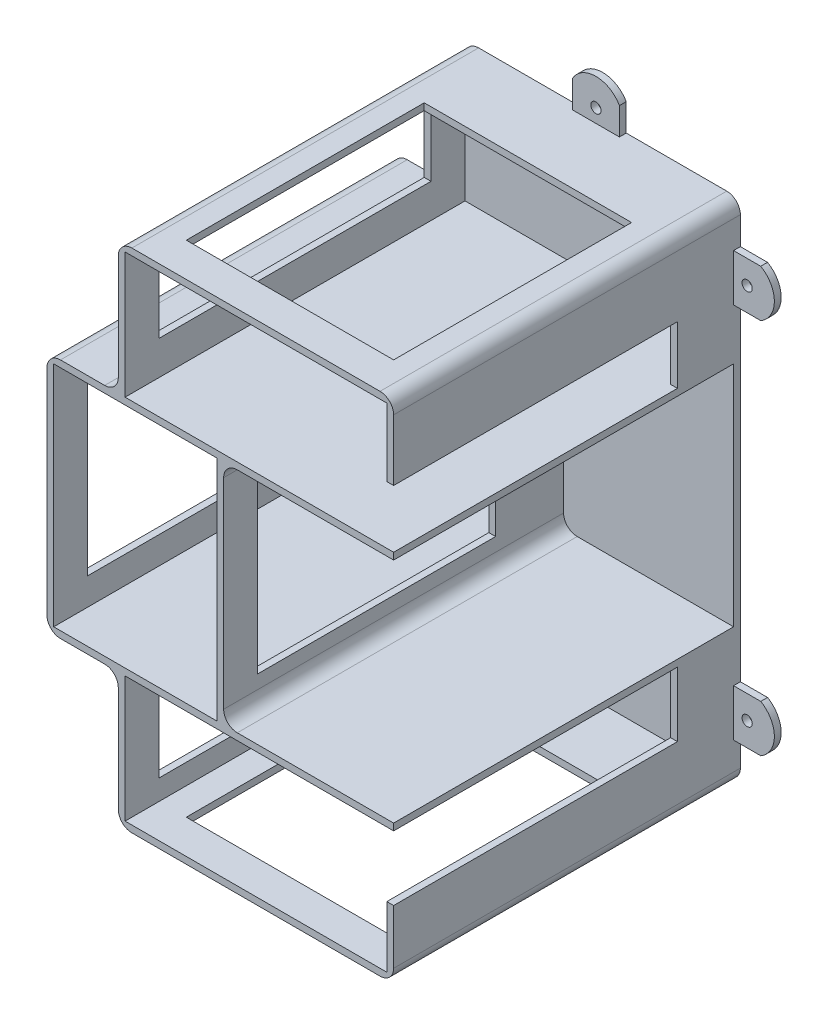
SolidWorks part; units mm, degrees
other "Marquage1"
sketch "Esquisse17" plane through (0, -52.2, -65) normal (-0.4358, -0.0146, -0.8999) x (-0.2736, 0.9547, 0.117)
ref_plane "Plan de face" through (0, 0, 0) normal (0, 0, 1) x (1, 0, 0)
ref_plane "Plan de dessus" through (0, 0, 0) normal (0, 1, 0) x (1, 0, 0)
ref_plane "Plan de droite" through (0, 0, 0) normal (1, 0, 0) x (0, 0, -1)
sketch "Esquisse27" plane through (0, 0, 0) normal (0, 0, 1) x (1, 0, 0)
  line L28 (148.5, -72.5) -> (67.5, -72.5)
  line L29 (67.5, -72.5) -> (67.5, -33.5)
  line L30 (148.5, 76.5) -> (67.5, 76.5)
  line L31 (67.5, 76.5) -> (67.5, 37.5)
  line L32 (67.5, -33.5) -> (46.5, -33.5)
  line L33 (46.5, -33.5) -> (46.5, 37.5)
  line L34 (46.5, 37.5) -> (67.5, 37.5)
  line L35 (148.5, 35.5) -> (98.5, 35.5)
  line L36 (98.5, 35.5) -> (98.5, -31.5)
  line L37 (98.5, -31.5) -> (148.5, -31.5)
  line L38 (148.5, 76.5) -> (148.5, 35.5)
  line L39 (148.5, -72.5) -> (148.5, -31.5)
  dimension "D1" = 81
  dimension "D2" = 149
  dimension "D3" = 71
  dimension "D4" = 50
  dimension "D5" = 21
  dimension "D6" = 76.5
  dimension "D7" = 81
  dimension "D8" = 67
  dimension "D9" = 50
  dimension "D10" = 41
  dimension "D11" = 39
  dimension "D12" = 39
  dimension "D13" = 21
  dimension "D14" = 46.5
extrude "Boss.-Extru.9" add sketch "Esquisse27" along normal blind 100
sketch "Esquisse31" plane through (0, 0, 100) normal (0, 0, 1) x (1, 0, 0)
  line L5 (148.5, -72.5) -> (148.5, -31.5) construction
  line L25 (148.5, -31.5) -> (98.5, -31.5) construction
  line L26 (46.5, 37.5) -> (46.5, -33.5) construction
  line L29 (98.5, -31.5) -> (98.5, 35.5) construction
  line L31 (67.5, -33.5) -> (67.5, -72.5) construction
  line L32 (67.5, -72.5) -> (148.5, -72.5) construction
  line L33 (148.5, 35.5) -> (148.5, 76.5) construction
  line L34 (98.5, 35.5) -> (148.5, 35.5) construction
  line L35 (148.5, 76.5) -> (67.5, 76.5) construction
  line L36 (67.5, 76.5) -> (67.5, 37.5) construction
  line L40 (69.5, 74.5) -> (69.5, 37.5)
  line L41 (48.5, -31.5) -> (48.5, 35.5)
  line L42 (69.5, -70.5) -> (69.5, -33.5)
  line L43 (146.5, 74.5) -> (69.5, 74.5)
  line L44 (146.5, 37.5) -> (146.5, 74.5)
  line L45 (96.5, 35.5) -> (96.5, -31.5)
  line L46 (146.5, -70.5) -> (146.5, -33.5)
  line L47 (69.5, -70.5) -> (146.5, -70.5)
  line L48 (96.5, -31.5) -> (48.5, -31.5)
  line L49 (96.5, 35.5) -> (48.5, 35.5)
  line L50 (146.5, -33.5) -> (69.5, -33.5)
  line L51 (146.5, 37.5) -> (69.5, 37.5)
  point P12 (109.5, 104.5)
  dimension "D1" = 2
  dimension "D2" = 2
  dimension "D3" = 2
  dimension "D4" = 2
  dimension "D5" = 2
  dimension "D6" = 2
  dimension "D7" = 2
  dimension "D8" = 2
  dimension "D9" = 2
  dimension "D10" = 2
  dimension "D11" = 2
  dimension "D12" = 2
extrude "Enlèv. mat.-Extru.17" cut sketch "Esquisse31" against normal blind 100
sketch "Esquisse35" plane through (0, -72.5, 0) normal (0, -1, 0) x (1, 0, 0)
  line L0 (148.5, 100) -> (148.5, 0) construction
  line L5 (67.5, 100) -> (67.5, 0) construction
  line L6 (67.5, 100) -> (148.5, 100) construction
  line L7 (67.5, 0) -> (148.5, 0) construction
  line L10 (77.5, 90) -> (138.5, 90)
  line L11 (77.5, 90) -> (77.5, 20)
  line L12 (77.5, 20) -> (138.5, 20)
  line L13 (138.5, 90) -> (138.5, 20)
  dimension "D1" = 10
  dimension "D2" = 10
  dimension "D3" = 10
  dimension "D4" = 20
extrude "Enlèv. mat.-Extru.20" cut sketch "Esquisse35" against normal blind 2
sketch "Esquisse36" plane through (67.5, 0, 0) normal (-1, 0, 0) x (0, 0, 1)
  line L0 (100, 76.5) -> (100, 37.5) construction
  line L2 (100, 76.5) -> (0, 76.5) construction
  line L3 (10, 47.5) -> (90, 47.5)
  line L4 (10, 47.5) -> (10, 68.5)
  line L5 (10, 68.5) -> (90, 68.5)
  line L6 (90, 47.5) -> (90, 68.5)
  line L7 (0, 76.5) -> (0, 37.5) construction
  line L8 (100, 37.5) -> (0, 37.5) construction
  line L14 (100, -33.5) -> (0, -33.5) construction
  line L25 (100, -33.5) -> (100, -72.5) construction
  line L26 (10, -64.5) -> (90, -64.5)
  line L27 (10, -64.5) -> (10, -43.5)
  line L28 (10, -43.5) -> (90, -43.5)
  line L29 (90, -64.5) -> (90, -43.5)
  line L30 (100, -72.5) -> (0, -72.5) construction
  line L32 (0, -33.5) -> (0, -72.5) construction
  point P2 (0, 69.5875)
  point P8 (97.8468, -33.5)
  point P9 (100, -57.2204)
  point P10 (79.7693, 37.5)
  point P18 (0, -48.009)
  point P19 (0, -42.1912)
  point P22 (100, -72.5)
  point P24 (76.4193, 76.5)
  point P26 (100, 53.6257)
  dimension "D1" = 8
  dimension "D2" = 10
  dimension "D3" = 10
  dimension "D4" = 10
  dimension "D5" = 8
  dimension "D6" = 10
  dimension "D7" = 10
  dimension "D8" = 10
sketch "Esquisse37" plane through (46.5, 0, 0) normal (-1, 0, 0) x (0, 0, 1)
  line L0 (-31.1815, 125) -> (105.2441, 125) construction
  line L1 (0, 37.5) -> (0, -33.5) construction
  line L2 (20, 27.5) -> (90, 27.5)
  line L3 (20, 27.5) -> (20, -23.5)
  line L4 (20, -23.5) -> (90, -23.5)
  line L5 (90, 27.5) -> (90, -23.5)
  line L6 (100, 37.5) -> (0, 37.5) construction
  line L7 (100, 37.5) -> (100, -33.5) construction
  line L8 (100, -33.5) -> (0, -33.5) construction
  dimension "D1" = 20
  dimension "D2" = 10
  dimension "D3" = 10
  dimension "D4" = 10
extrude "Enlèv. mat.-Extru.22" cut sketch "Esquisse37" against normal blind 52
sketch "Esquisse38" plane through (0, 76.5, 0) normal (0, 1, 0) x (1, 0, 0)
  line L0 (148.5, -100) -> (148.5, 0) construction
  line L5 (148.5, 0) -> (67.5, 0) construction
  line L6 (148.5, -100) -> (67.5, -100) construction
  line L7 (67.5, -100) -> (67.5, 0) construction
  line L12 (77.5, -90) -> (138.5, -90)
  line L13 (77.5, -90) -> (77.5, -20)
  line L14 (77.5, -20) -> (138.5, -20)
  line L15 (138.5, -90) -> (138.5, -20)
  dimension "D1" = 10
  dimension "D2" = 20
  dimension "D3" = 10
  dimension "D4" = 10
extrude "Enlèv. mat.-Extru.23" cut sketch "Esquisse38" against normal blind 2
sketch "Esquisse39" plane through (148.5, 0, 0) normal (1, 0, 0) x (0, 0, -1)
  line L5 (-100, 35.5) -> (-100, 76.5) construction
  line L14 (-100, 54.5) -> (-16.5, 54.5)
  line L20 (-100, 76.5) -> (0, 76.5) construction
  line L23 (-100, -52.5) -> (-16.5, -52.5)
  line L35 (-100, -72.5) -> (0, -72.5) construction
  line L40 (0, 35.5) -> (0, 76.5) construction
  line L41 (-16.5, 54.5) -> (-16.5, 37.5)
  line L42 (-16.5, 37.5) -> (-100, 37.5)
  line L43 (-100, 37.5) -> (-100, 54.5)
  line L44 (-100, 35.5) -> (0, 35.5) construction
  line L45 (0, -72.5) -> (0, -31.5) construction
  line L46 (-16.5, -52.5) -> (-16.5, -33.5)
  line L47 (-16.5, -33.5) -> (-100, -33.5)
  line L48 (-100, -72.5) -> (-100, -31.5) construction
  line L49 (-100, -33.5) -> (-100, -52.5)
  line L50 (-100, -31.5) -> (0, -31.5) construction
  dimension "D1" = 16.5
  dimension "D2" = 16.5
  dimension "D3" = 22
  dimension "D4" = 2
  dimension "D5" = 2
  dimension "D6" = 20
extrude "Enlèv. mat.-Extru.25" cut sketch "Esquisse36" against normal blind 2
extrude "Enlèv. mat.-Extru.26" cut sketch "Esquisse39" against normal blind 2
sketch "Esquisse46" plane through (0, 0, 0) normal (0, 0, -1) x (-1, 0, 0)
  line L0 (-148.5, 64.3564) -> (-148.5, 76.5)
  line L1 (-148.5, 76.5) -> (-114.9282, 76.5)
  line L2 (-101.0718, 76.5) -> (-67.5, 76.5)
  line L3 (-67.5, 76.5) -> (-67.5, 68.5)
  line L4 (-114.9282, 76.5) -> (-114.9282, 84.5)
  line L5 (-101.0718, 84.5) -> (-101.0718, 76.5)
  line L6 (-67.5, 47.2) -> (-67.5, 37.5)
  line L7 (-67.5, -64.5) -> (-67.5, -72.5)
  line L8 (-100.97, -72.5) -> (-67.5, -72.5)
  line L10 (-114.9282, 80.5) -> (-101.0718, 80.5) construction
  line L11 (-148.5, 64.3564) -> (-156.5, 64.3564)
  line L12 (-156.5, 50.5) -> (-148.5, 50.5)
  line L13 (-152.5, 64.3564) -> (-152.5, 50.5) construction
  line L14 (-67.5, 68.5) -> (-61.5, 68.5)
  line L15 (-67.5, 37.5) -> (-46.5, 37.5)
  line L16 (-148.5, 50.5) -> (-148.5, -46.5)
  line L17 (-156.5, -46.5) -> (-148.5, -46.5)
  line L18 (-67.5, -64.5) -> (-61.6018, -64.5)
  line L20 (-46.5, 37.5) -> (-46.5, -33.5)
  line L21 (-67.5, -33.5) -> (-67.5, -72.5) construction
  line L26 (-67.5, -72.5) -> (-148.5, -72.5) construction
  line L28 (-67.5, -43.1998) -> (-67.5, -33.5)
  line L29 (-67.5, -33.5) -> (-46.5, -33.5)
  line L30 (-61.5, 68.5) -> (-61.5, 59.8)
  line L31 (-61.6018, -64.5) -> (-61.6018, -55.8485)
  line L35 (-67.5, 76.5) -> (-67.5, 37.5) construction
  line L43 (-148.5, -60.3564) -> (-156.5, -60.3564)
  line L44 (-148.5, -72.5) -> (-148.5, -60.3564)
  line L45 (-148.5, -72.5) -> (-114.8264, -72.5)
  line L46 (-114.8264, -72.5) -> (-114.8264, -80.5)
  line L47 (-100.97, -80.5) -> (-100.97, -72.5)
  line L49 (-61.5, 47.2) -> (-67.5, 47.2)
  line L54 (-67.5, -43.1998) -> (-61.5, -43.1998)
  circle A0 centre (-108, 80.5) radius 1.5
  circle A1 centre (-152.5, 57.4282) radius 1.5
  circle A2 centre (-64.5512, 53.5) radius 1.5
  circle A3 centre (-64.5508, -49.5) radius 1.5
  arc A8 (-61.5, 59.8) -> (-61.5, 47.2) centre (-64.5512, 53.5) cw
  arc A9 (-61.5, -43.1998) -> (-61.6018, -55.8485) centre (-64.5508, -49.5) cw
  arc A21 (-114.9282, 84.5) -> (-101.0718, 84.5) centre (-108, 80.5) cw
  arc A22 (-156.5, 64.3564) -> (-156.5, 50.5) centre (-152.5, 57.4282) ccw
  circle A23 centre (-152.5, -53.4282) radius 1.5
  arc A24 (-156.5, -60.3564) -> (-156.5, -46.5) centre (-152.5, -53.4282) cw
  circle A25 centre (-107.8982, -76.5) radius 1.5
  arc A26 (-114.8264, -80.5) -> (-100.97, -80.5) centre (-107.8982, -76.5) ccw
  point P5 (-67.5, -33.5)
  point P6 (-67.6018, 37.5)
  point P7 (-67.5, 76.5)
  point P10 (-67.5, 68.5)
  point P11 (-67.5, 47.1782)
  point P70 (-148.5, 2)
  point P111 (-148.5, 2)
  dimension "D1" = 3
  dimension "D2" = 3
  dimension "D6" = 3
  dimension "D8" = 6
  dimension "D9" = 0
  dimension "D11" = 8
  dimension "D12" = 3
  dimension "D14" = 7
  dimension "D15" = 7
  dimension "D16" = 12.6491
  dimension "D17" = 5.8982
  dimension "D19" = 0
  dimension "D20" = 9.7
  dimension "D22" = 8
  dimension "D24" = 8
  dimension "D13" = 15
  dimension "D3" = 8
  dimension "D4" = 6
  dimension "D5" = 8
  dimension "D7" = 15
  dimension "D10" = 0
  dimension "D18" = 0
  dimension "D23" = 8
  dimension "D31" = 12.1436
  dimension "D32" = 33.5718
  dimension "D34" = 6
  dimension "D42" = 97
extrude "Boss.-Extru.10" add sketch "Esquisse46" along normal blind 2
fillet "Congé59" radius 4 12 edges at (61.6018, -64.5, -1) (61.5, 68.5, -1) (67.5, -33.5, 49) (148.5, -72.5, 49) (98.5, -31.5, 50) (98.5, 35.5, 50) (148.5, 76.5, 49) (67.5, 76.5, 49) (67.5, -72.5, 49) (46.5, -33.5, 49) (46.5, 37.5, 49) (67.5, 37.5, 49)
